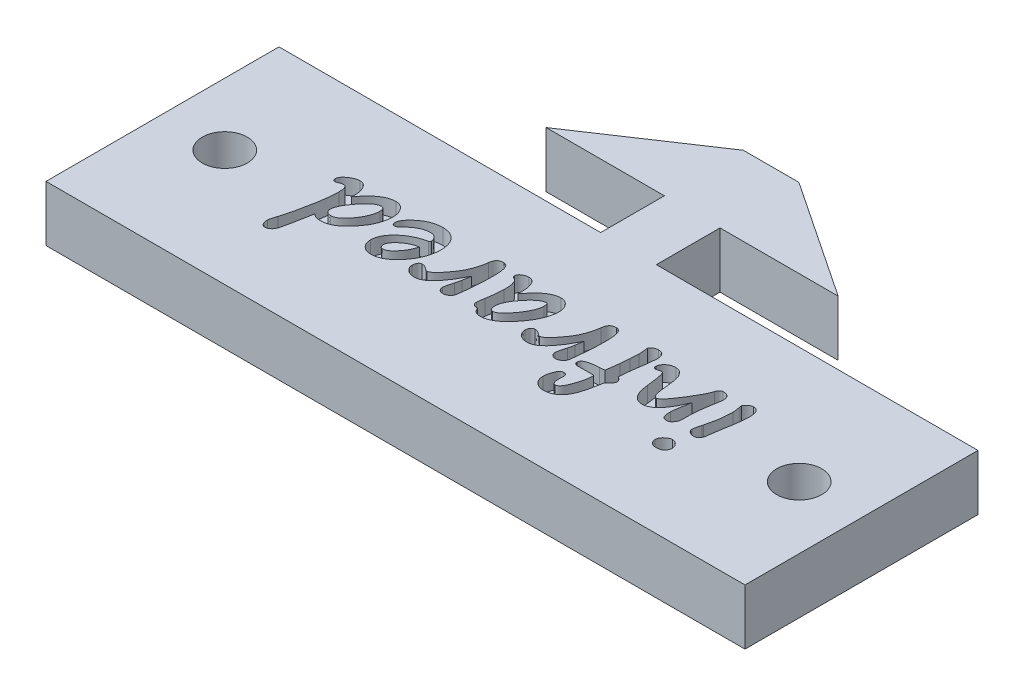
SolidWorks part; units mm, degrees
ref_plane "Front" through (0, 0, 0) normal (0, 0, 1) x (1, 0, 0)
ref_plane "Top" through (0, 0, 0) normal (0, 1, 0) x (1, 0, 0)
ref_plane "Right" through (0, 0, 0) normal (1, 0, 0) x (0, 0, -1)
sketch "Sketch1" plane through (0, 0, 0) normal (0, 1, 0) x (1, 0, 0)
  line L0 (-1.7907, 2.05) -> (-9.398, 2.05)
  line L2 (-1.7907, -2.05) -> (-1.7907, 2.05)
  line L4 (1.7907, -2.05) -> (1.7907, 2.05)
  line L7 (-9.398, 2.05) -> (-1.7907, 7.13)
  line L8 (-1.7907, 7.13) -> (1.7907, 7.13)
  line L9 (1.7907, 7.13) -> (9.398, 2.05)
  line L10 (9.398, 2.05) -> (1.7907, 2.05)
  line L11 (1.7907, -2.05) -> (22.5, -2.05)
  line L12 (-1.7907, -2.05) -> (-22.5, -2.05)
  line L13 (-22.5, -2.05) -> (-22.5, -17.05)
  line L14 (-22.5, -17.05) -> (22.5, -17.05)
  line L15 (22.5, -17.05) -> (22.5, -2.05)
  line L16 (22.5, -2.05) -> (1.7907, -2.05)
  point P0 (0, 0)
  point P17 (0, 7.13)
  point P19 (0, -17.05)
  point P24 (1.7907, 0)
  dimension "D1" = 18.796
  dimension "D2" = 3.5814
  dimension "D3" = 45
  dimension "D4" = 15
  dimension "D5" = 5.08
  dimension "D7" = 4.1
extrude "Boss-Extrude1" add sketch "Sketch1" along normal blind 3.5814 contours L14 L15 L11 L4 L10 L9 L8 L7 L0 L2 L12 L13
sketch "Sketch2" plane through (0, 3.5814, 0) normal (0, 1, 0) x (1, 0, 0)
  line L0 (0, 0) -> (0, -15.3387) construction
  line L2 (-22.5, -2.05) -> (-22.5, -17.05) construction
  circle A0 centre (-18.49, -9.55) radius 1.45
  circle A1 centre (18.49, -9.55) radius 1.45
  point P11 (-22.5, -9.55)
  dimension "D1" = 2.9
  dimension "D2" = 18.49
extrude "Cut-Extrude1" cut sketch "Sketch2" against normal through all
sketch "infraredText" plane through (0, 3.5814, 0) normal (0, 1, 0) x (1, 0, 0)
  line L0 (-22.4401, -7.0312) -> (22.5599, -7.0312) construction
  text T0 "infrared" font "Segoe Print" height in points 16
  point P3 (-22.4978, -7.9542)
  point P4 (22.5555, -8.1849)
  point P5 (-22.4401, -7.0312)
  point P6 (22.5844, -6.7139)
  dimension "D1" = 45
extrude "Cut-Extrude3" cut sketch "infraredText" against normal blind 1
